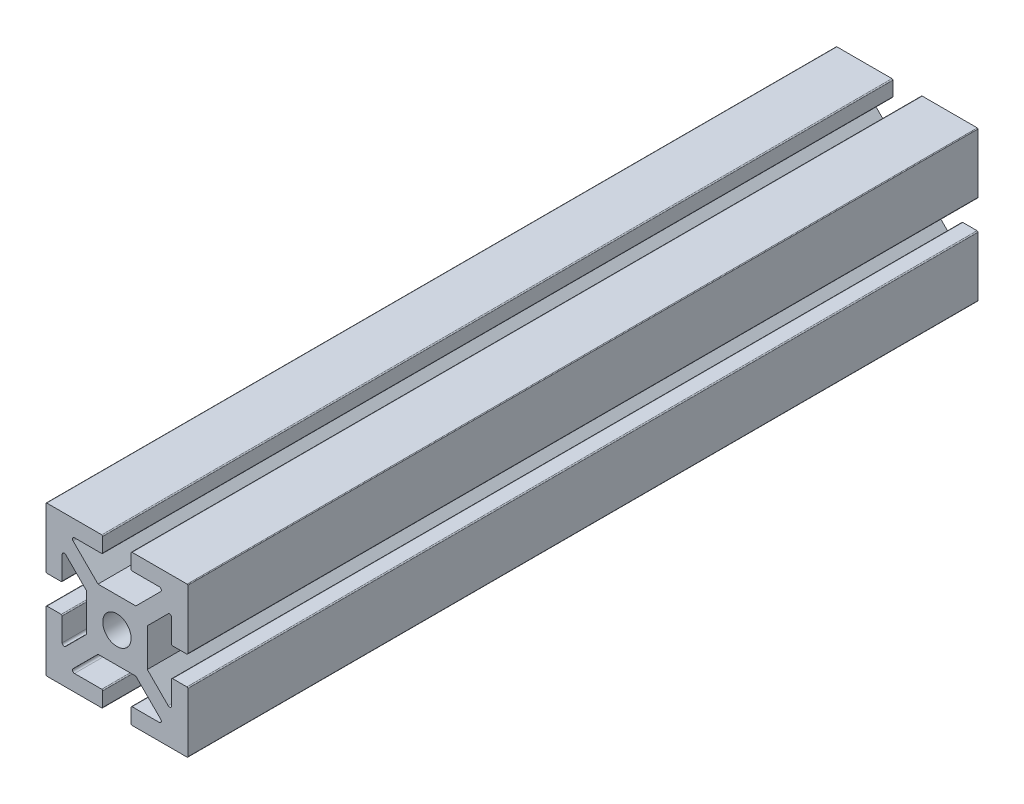
SolidWorks part; units mm, degrees
ref_plane "Front Plane" through (0, 0, 0) normal (0, 0, 1) x (1, 0, 0)
ref_plane "Top Plane" through (0, 0, 0) normal (0, 1, 0) x (1, 0, 0)
ref_plane "Right Plane" through (0, 0, 0) normal (1, 0, 0) x (0, 0, -1)
sketch "Sketch1" plane through (0, 0, 0) normal (0, 0, 1) x (1, 0, 0)
  line L0 (-110.0237, 0) -> (99.4895, 0) construction
  line L1 (-3.5, 0) -> (-3.5, 10.5928) construction
  line L2 (3.5, 0) -> (3.5, 10.5928) construction
  line L4 (0, -3.5) -> (-10.505, -3.5) construction
  line L5 (-10.505, -3.5) -> (-10.505, 3.5) construction
  line L8 (0, 27.4572) -> (0, -34.2656) construction
  line L10 (-3.5, 10.5928) -> (3.5, 10.5928) construction
  line L12 (-10.505, 3.5) -> (0, 3.5) construction
  line L15 (-7.5, -4.6716) -> (-7.5, 4.6716)
  line L26 (7.5, -4.6716) -> (7.5, 4.6716)
  line L27 (4.6716, 7.5) -> (10.818, 13.6464)
  line L36 (12.6464, 9.818) -> (7.5, 4.6716)
  line L37 (3.75, 14.5) -> (10.4645, 14.5)
  line L38 (3.5, 18.25) -> (3.5, 14.75)
  line L39 (3.75, 18.5) -> (17.3232, 18.5)
  line L40 (17.5, 3.75) -> (17.5, 18.3232)
  line L41 (17.25, 3.5) -> (13.75, 3.5)
  line L42 (13.5, 9.4645) -> (13.5, 3.75)
  line L72 (0, 0) -> (22.505, 22.505) construction
  line L74 (-3.5, 3.7) -> (0, 0) construction
  line L76 (-4.6716, 7.5) -> (4.6716, 7.5)
  line L77 (-12.6464, 9.818) -> (-7.5, 4.6716)
  line L78 (-13.5, 9.4645) -> (-13.5, 3.75)
  line L79 (-17.25, 3.5) -> (-13.75, 3.5)
  line L80 (-17.5, 3.75) -> (-17.5, 18.3232)
  line L81 (-3.75, 18.5) -> (-17.3232, 18.5)
  line L82 (-3.5, 18.25) -> (-3.5, 14.75)
  line L83 (-3.75, 14.5) -> (-10.4645, 14.5)
  line L84 (-4.6716, 7.5) -> (-10.818, 13.6464)
  line L85 (-17.5, -3.75) -> (-17.5, -18.3232)
  line L86 (-17.25, -3.5) -> (-13.75, -3.5)
  line L87 (-13.5, -9.4645) -> (-13.5, -3.75)
  line L88 (-12.6464, -9.818) -> (-7.5, -4.6716)
  line L89 (12.6464, -9.818) -> (7.5, -4.6716)
  line L90 (13.5, -9.4645) -> (13.5, -3.75)
  line L91 (17.25, -3.5) -> (13.75, -3.5)
  line L92 (17.5, -3.75) -> (17.5, -18.3232)
  line L93 (-3.5, -10.5928) -> (3.5, -10.5928) construction
  line L94 (-4.6716, -7.5) -> (-10.818, -13.6464)
  line L95 (-3.75, -14.5) -> (-10.4645, -14.5)
  line L96 (-3.5, -18.25) -> (-3.5, -14.75)
  line L97 (-3.75, -18.5) -> (-17.3232, -18.5)
  line L98 (-4.6716, -7.5) -> (4.6716, -7.5)
  line L99 (3.75, -18.5) -> (17.3232, -18.5)
  line L100 (3.5, -18.25) -> (3.5, -14.75)
  line L101 (3.75, -14.5) -> (10.4645, -14.5)
  line L102 (4.6716, -7.5) -> (10.818, -13.6464)
  circle A0 centre (0, 0) radius 3.5
  arc A1 (17.3232, 18.5) -> (17.5, 18.3232) centre (17.3232, 18.3232) cw
  arc A4 (17.5, 3.75) -> (17.25, 3.5) centre (17.25, 3.75) cw
  arc A5 (13.75, 3.5) -> (13.5, 3.75) centre (13.75, 3.75) cw
  arc A9 (3.75, 14.5) -> (3.5, 14.75) centre (3.75, 14.75) cw
  arc A10 (3.5, 18.25) -> (3.75, 18.5) centre (3.75, 18.25) cw
  arc A11 (12.6464, 9.818) -> (13.5, 9.4645) centre (13, 9.4645) cw
  arc A12 (10.818, 13.6464) -> (10.4645, 14.5) centre (10.4645, 14) ccw
  arc A33 (-13.75, 3.5) -> (-13.5, 3.75) centre (-13.75, 3.75) ccw
  arc A34 (-17.5, 3.75) -> (-17.25, 3.5) centre (-17.25, 3.75) ccw
  arc A35 (-10.818, 13.6464) -> (-10.4645, 14.5) centre (-10.4645, 14) cw
  arc A36 (-12.6464, 9.818) -> (-13.5, 9.4645) centre (-13, 9.4645) ccw
  arc A37 (-3.5, 18.25) -> (-3.75, 18.5) centre (-3.75, 18.25) ccw
  arc A38 (-3.75, 14.5) -> (-3.5, 14.75) centre (-3.75, 14.75) ccw
  arc A39 (-17.3232, 18.5) -> (-17.5, 18.3232) centre (-17.3232, 18.3232) ccw
  arc A40 (13.75, -3.5) -> (13.5, -3.75) centre (13.75, -3.75) ccw
  arc A41 (17.5, -3.75) -> (17.25, -3.5) centre (17.25, -3.75) ccw
  arc A42 (-17.5, -3.75) -> (-17.25, -3.5) centre (-17.25, -3.75) cw
  arc A43 (-13.75, -3.5) -> (-13.5, -3.75) centre (-13.75, -3.75) cw
  arc A44 (-17.3232, -18.5) -> (-17.5, -18.3232) centre (-17.3232, -18.3232) cw
  arc A45 (-3.75, -14.5) -> (-3.5, -14.75) centre (-3.75, -14.75) cw
  arc A46 (-3.5, -18.25) -> (-3.75, -18.5) centre (-3.75, -18.25) cw
  arc A47 (-12.6464, -9.818) -> (-13.5, -9.4645) centre (-13, -9.4645) cw
  arc A48 (-10.818, -13.6464) -> (-10.4645, -14.5) centre (-10.4645, -14) ccw
  arc A49 (10.818, -13.6464) -> (10.4645, -14.5) centre (10.4645, -14) cw
  arc A50 (12.6464, -9.818) -> (13.5, -9.4645) centre (13, -9.4645) ccw
  arc A51 (3.5, -18.25) -> (3.75, -18.5) centre (3.75, -18.25) ccw
  arc A52 (3.75, -14.5) -> (3.5, -14.75) centre (3.75, -14.75) ccw
  arc A53 (17.3232, -18.5) -> (17.5, -18.3232) centre (17.3232, -18.3232) ccw
  point P5 (0, 0)
  point P12 (0, 0)
  point P20 (0, 0)
  point P25 (13.5, 10.6716)
  point P27 (0, 0)
  point P31 (0, 0)
  point P32 (17.5, 18.5)
  point P35 (0, 0)
  point P36 (-5.2671, 0)
  point P52 (17.5, 3.5)
  point P55 (13.5, 3.5)
  point P58 (0, 7.5)
  point P67 (3.5, 14.5)
  point P70 (3.5, 18.5)
  point P72 (11.6716, 14.5)
  point P79 (-11.6716, 14.5)
  point P80 (-3.5, 18.5)
  point P81 (-3.5, 14.5)
  point P82 (-17.5, 18.5)
  point P83 (-13.5, 10.6716)
  point P130 (-13.5, -10.6716)
  point P131 (-17.5, -18.5)
  point P132 (-3.5, -14.5)
  point P133 (-3.5, -18.5)
  point P134 (-11.6716, -14.5)
  point P135 (11.6716, -14.5)
  point P136 (3.5, -18.5)
  point P137 (3.5, -14.5)
  point P138 (0, -7.5)
  point P139 (17.5, -18.5)
  point P141 (13.5, -10.6716)
  point P142 (-13.5, -6.6072)
  dimension "D1" = 7
  dimension "D7" = 0.25
  dimension "D2" = 4
  dimension "D3" = 4
  dimension "D9" = 7.5
  dimension "D12" = 3.5
  dimension "D13" = 0.25
  dimension "D15" = 45
  dimension "D16" = 2
  dimension "D4" = 7.5
  dimension "D5" = 7
  dimension "D8" = 7
  dimension "D10" = 17.5
  dimension "D11" = 13.5
  dimension "D14" = 45
  dimension "D17" = 0.5
extrude "Boss-Extrude1" add sketch "Sketch1" along normal blind 195
equation "\"a\"= 4mm"
equation "\"b\"= 7mm"
equation "\"c\"= 195mm"
equation "\"d\"= ( \"b\" / 2 ) + \"a\""
equation "\"D1@Sketch1\"=\"b\""
equation "\"D2@Sketch1\"=\"a\""
equation "\"D9@Sketch1\"=\"d\""
equation "\"D3@Sketch1\"=\"a\""
equation "\"D16@Sketch1\"=\"a\"/2"
equation "\"D4@Sketch1\"=\"d\""
equation "\"D5@Sketch1\"=\"b\""
equation "\"D8@Sketch1\"=\"b\""
